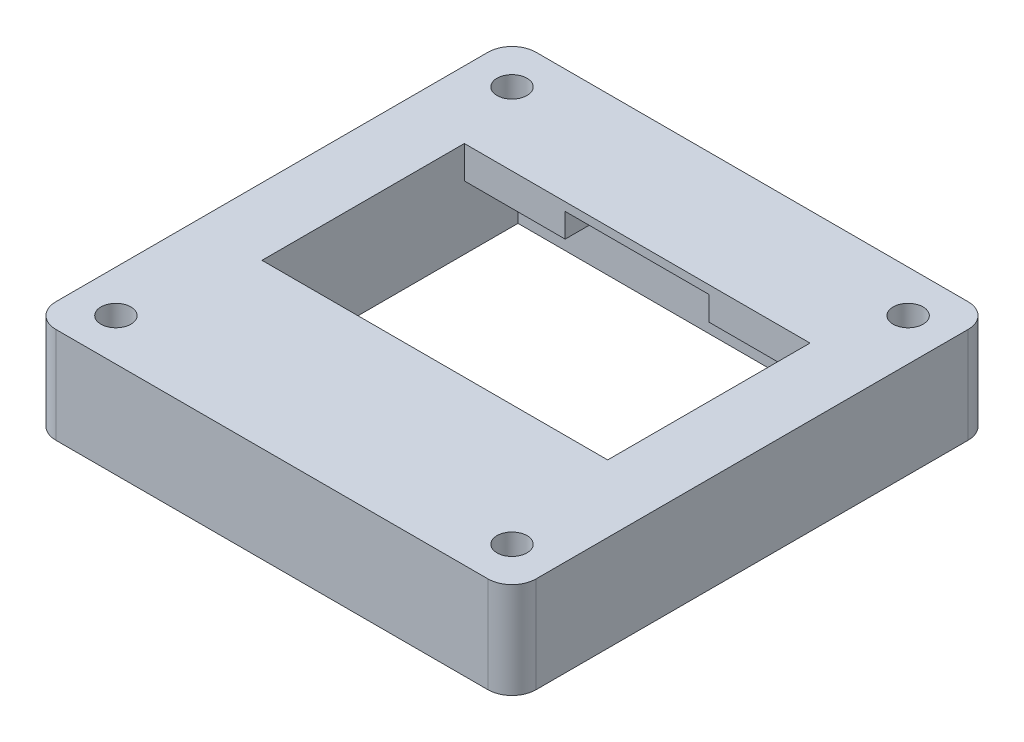
SolidWorks part; units mm, degrees
ref_plane "Спереди" through (0, 0, 0) normal (0, 0, 1) x (1, 0, 0)
ref_plane "Сверху" through (0, 0, 0) normal (0, 1, 0) x (1, 0, 0)
ref_plane "Справа" through (0, 0, 0) normal (1, 0, 0) x (0, 0, -1)
sketch "габариты дисплея" plane through (0, 0, 0) normal (0, 1, 0) x (1, 0, 0)
  line L1 (-13.6, -13.6) -> (13.6, -13.6)
  line L2 (-13.6, -13.6) -> (-13.6, 13.6)
  line L3 (-13.6, 13.6) -> (13.6, 13.6)
  line L4 (13.6, -13.6) -> (13.6, 13.6)
  line L5 (-13.6, -13.6) -> (13.6, 13.6) construction
  line L6 (-13.6, 13.6) -> (13.6, -13.6) construction
  line L7 (-13.6, -9.63) -> (13.6, -9.63)
  line L8 (-13.6, -9.63) -> (-13.6, 9.63)
  line L9 (-13.6, 9.63) -> (13.6, 9.63)
  line L10 (13.6, -9.63) -> (13.6, 9.63)
  line L11 (-13.6, -9.63) -> (13.6, 9.63) construction
  line L12 (-13.6, 9.63) -> (13.6, -9.63) construction
  line L13 (-11.6, -11.6) -> (11.6, -11.6) construction
  line L14 (-11.6, -11.6) -> (-11.6, 11.6) construction
  line L15 (-11.6, 11.6) -> (11.6, 11.6) construction
  line L16 (11.6, -11.6) -> (11.6, 11.6) construction
  line L17 (-11.6, -11.6) -> (11.6, 11.6) construction
  line L18 (-11.6, 11.6) -> (11.6, -11.6) construction
  circle A0 centre (-11.6, 11.6) radius 1.25
  circle A1 centre (11.6, 11.6) radius 1.25
  circle A2 centre (11.6, -11.6) radius 1.25
  circle A3 centre (-11.6, -11.6) radius 1.25
  point P0 (0, 0)
  point P6 (0, 0)
  point P12 (0, 0)
  dimension "D5" = 2.5
  dimension "D1" = 19.26
  dimension "D2" = 27.2
  dimension "D3" = 27.2
  dimension "D4" = 2
sketch "Эскиз1" plane through (0, 0, 0) normal (0, 1, 0) x (1, 0, 0)
  line L1 (-20, 20) -> (20, 20)
  line L2 (-20, 20) -> (-20, -20)
  line L3 (-20, -20) -> (20, -20)
  line L4 (20, 20) -> (20, -20)
  line L5 (-20, 20) -> (20, -20) construction
  line L6 (-20, -20) -> (20, 20) construction
  point P0 (0, 0)
  dimension "D1" = 40
  dimension "D2" = 40
extrude "тело" add sketch "Эскиз1" along normal blind 8
sketch "Эскиз2" plane through (0, 0, 0) normal (0, -1, 0) x (1, 0, 0)
  line L0 (-13.6, 13.6) -> (13.6, 13.6) construction
  line L1 (-14.4, -14.9) -> (14.4, -14.9)
  line L2 (-14.4, -14.9) -> (-14.4, 14.9)
  line L3 (-14.4, 14.9) -> (14.4, 14.9)
  line L4 (14.4, -14.9) -> (14.4, 14.9)
  line L5 (-14.4, -14.9) -> (14.4, 14.9) construction
  line L6 (-14.4, 14.9) -> (14.4, -14.9) construction
  line L7 (13.6, 13.6) -> (13.6, -13.6) construction
  point P0 (0, 0)
  dimension "D1" = 1.3
  dimension "D2" = 0.8
extrude "углубление для платы" cut sketch "Эскиз2" against normal offset from surface (5.3 mm away) 2.7 up to face at (0, 8, 0)
sketch "Эскиз3" plane through (0, 5.3, 0) normal (0, -1, 0) x (1, 0, 0)
  line L0 (14.4, -14.9) -> (14.4, 14.9) construction
  line L1 (-14.4, -10.43) -> (14.4, -10.43)
  line L2 (-14.4, -10.43) -> (-14.4, 10.43)
  line L3 (-14.4, 10.43) -> (14.4, 10.43)
  line L4 (14.4, -10.43) -> (14.4, 10.43)
  line L5 (-14.4, -10.43) -> (14.4, 10.43) construction
  line L6 (-14.4, 10.43) -> (14.4, -10.43) construction
  line L7 (-13.6, 9.63) -> (13.6, 9.63) construction
  point P0 (0, 0)
  dimension "D1" = 0.8
extrude "отверстие для дисплея" cut sketch "Эскиз3" against normal through all
sketch "Эскиз4" plane through (0, 5.3, 0) normal (0, -1, 0) x (1, 0, 0)
  line L0 (14.4, 10.43) -> (-14.4, 10.43) construction
  line L1 (-6, 10.43) -> (6, 10.43)
  line L2 (-6, 10.43) -> (-6, 14.9)
  line L3 (-6, 14.9) -> (6, 14.9)
  line L4 (6, 10.43) -> (6, 14.9)
  line L5 (14.4, 14.9) -> (-14.4, 14.9) construction
  line L6 (-14.4, -10.43) -> (14.4, -10.43) construction
  line L7 (6, -10.43) -> (-6, -10.43)
  line L8 (6, -10.43) -> (6, -14.9)
  line L9 (6, -14.9) -> (-6, -14.9)
  line L10 (-6, -10.43) -> (-6, -14.9)
  line L11 (-14.4, -14.9) -> (14.4, -14.9) construction
  point P16 (0, -10.43)
  point P18 (0, 10.43)
  dimension "D1" = 12
extrude "углубление для шлейфа и пинов" cut sketch "Эскиз4" against normal offset from surface (2 mm away) 0.7 up to face at (0, 8, 0)
sketch "Эскиз5" plane through (0, 0, 10.43) normal (0, 0, -1) x (-1, 0, 0)
  line L1 (-14.4, 8) -> (-14.4, 5.3) construction
  line L2 (14.4, 8) -> (-14.4, 8)
  line L3 (14.4, 8) -> (14.4, 7.5)
  line L4 (14.4, 7.5) -> (-14.4, 7.5)
  line L6 (-14.4, 8) -> (-14.4, 7.5)
  dimension "D1" = 0.5
extrude "щит нижней части дисплея" add sketch "Эскиз5" along normal blind 4
sketch "Эскиз7" plane through (0, 0, 0) normal (0, -1, 0) x (1, 0, 0)
  line L1 (-16.5, -16.5) -> (16.5, -16.5) construction
  line L2 (-16.5, -16.5) -> (-16.5, 16.5) construction
  line L3 (-16.5, 16.5) -> (16.5, 16.5) construction
  line L4 (16.5, -16.5) -> (16.5, 16.5) construction
  line L5 (-16.5, -16.5) -> (16.5, 16.5) construction
  line L6 (-16.5, 16.5) -> (16.5, -16.5) construction
  circle A0 centre (-16.5, 16.5) radius 1.25
  circle A1 centre (16.5, 16.5) radius 1.25
  circle A2 centre (16.5, -16.5) radius 1.25
  circle A3 centre (-16.5, -16.5) radius 1.25
  point P0 (0, 0)
  dimension "D3" = 2.5
  dimension "D1" = 33
  dimension "D2" = 33
extrude "крепежные отверстия" cut sketch "Эскиз7" against normal through all
fillet "Скругление1" radius 2 4 edges at (-20, 4, -20) (20, 4, -20) (20, 4, 20) (-20, 4, 20)
